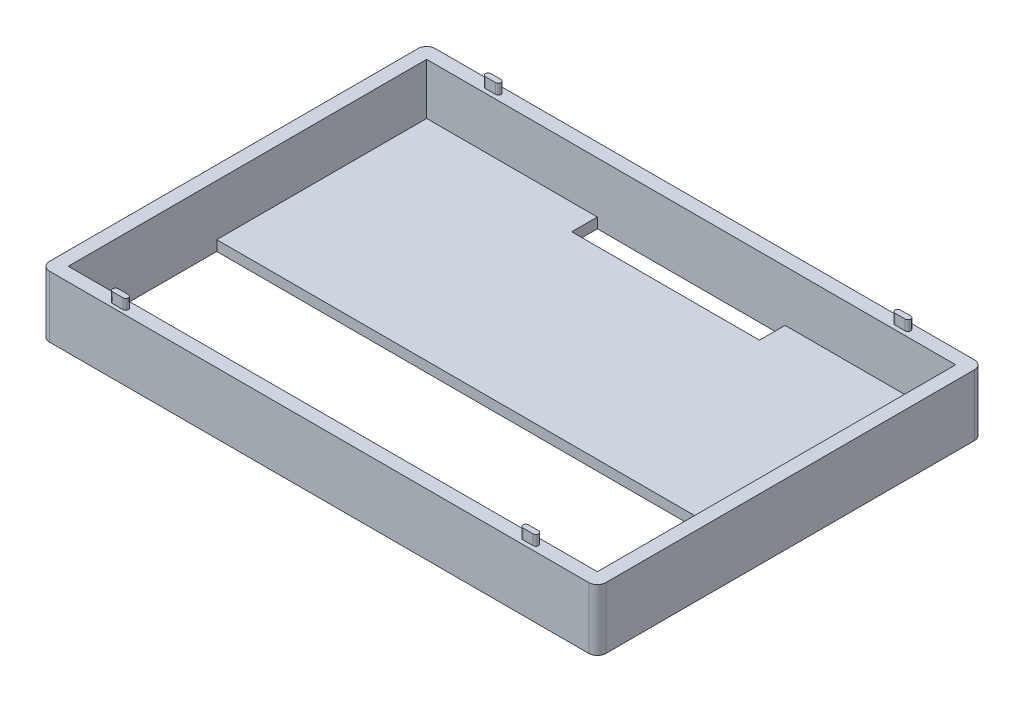
SolidWorks part; units mm, degrees
ref_plane "Front Plane" through (0, 0, 0) normal (0, 0, 1) x (1, 0, 0)
ref_plane "Top Plane" through (0, 0, 0) normal (0, 1, 0) x (1, 0, 0)
ref_plane "Right Plane" through (0, 0, 0) normal (1, 0, 0) x (0, 0, -1)
sketch "Sketch3" plane through (0, 0, 0) normal (0, 1, 0) x (1, 0, 0)
  line L1 (-81.5, 56.5) -> (81.5, 56.5)
  line L2 (-81.5, 56.5) -> (-81.5, -56.5)
  line L3 (-81.5, -56.5) -> (81.5, -56.5)
  line L4 (81.5, 56.5) -> (81.5, -56.5)
  line L5 (-81.5, 56.5) -> (81.5, -56.5) construction
  line L6 (-81.5, -56.5) -> (81.5, 56.5) construction
  point P0 (0, 0)
  dimension "D1" = 113
  dimension "D2" = 163
extrude "Boss-Extrude2" add sketch "Sketch3" along normal blind 18
sketch "Sketch4" plane through (0, 18, 0) normal (0, 1, 0) x (1, 0, 0)
  line L1 (-77.5, 52.5) -> (77.5, 52.5)
  line L2 (-77.5, 52.5) -> (-77.5, -52.5)
  line L3 (-77.5, -52.5) -> (77.5, -52.5)
  line L4 (77.5, 52.5) -> (77.5, -52.5)
  line L5 (-77.5, 52.5) -> (77.5, -52.5) construction
  line L6 (-77.5, -52.5) -> (77.5, 52.5) construction
  point P0 (0, 0)
  dimension "D1" = 105
  dimension "D2" = 155
extrude "Cut-Extrude2" cut sketch "Sketch4" against normal blind 15
fillet "Fillet1" radius 2.5 4 edges at (81.5, 9, -56.5) (-81.5, 9, -56.5) (81.5, 9, 56.5) (-81.5, 9, 56.5)
sketch "Sketch5" plane through (0, 3, 0) normal (0, 1, 0) x (1, 0, 0)
  line L0 (77.5, 52.5) -> (-77.5, 52.5) construction
  line L1 (27.5, 52.5) -> (-27.5, 52.5)
  line L2 (27.5, 52.5) -> (27.5, 45)
  line L3 (27.5, 45) -> (-27.5, 45)
  line L4 (-27.5, 52.5) -> (-27.5, 45)
  line L5 (-77.5, 52.5) -> (-77.5, -52.5) construction
  dimension "D1" = 7.5
  dimension "D2" = 55
  dimension "D3" = 50
extrude "TopWires" cut sketch "Sketch5" against normal blind 3
sketch "Sketch6" plane through (0, 3, 0) normal (0, 1, 0) x (1, 0, 0)
  line L0 (77.5, -52.5) -> (77.5, 52.5) construction
  line L1 (-77.5, -52.5) -> (77.5, -52.5)
  line L2 (-77.5, -52.5) -> (-77.5, -9)
  line L3 (-77.5, -9) -> (77.5, -9)
  line L4 (77.5, -52.5) -> (77.5, -9)
  dimension "D1" = 43.5
extrude "MotorWires" cut sketch "Sketch6" against normal blind 3
sketch "Sketch13" plane through (0, 0, 0) normal (0, -1, 0) x (-1, 0, 0)
  line L0 (61.5, 54.5) -> (58.5, 54.5) construction
  line L1 (61.5, 53.5) -> (58.5, 53.5)
  line L2 (61.5, 55.5) -> (58.5, 55.5)
  line L3 (-79, 56.5) -> (79, 56.5) construction
  line L4 (81.5, 54) -> (81.5, -54) construction
  line L5 (-58.5, 54.5) -> (-61.5, 54.5) construction
  line L6 (-58.5, 53.5) -> (-61.5, 53.5)
  line L7 (-58.5, 55.5) -> (-61.5, 55.5)
  line L8 (-81.5, -54) -> (-81.5, 54) construction
  line L9 (61.5, -54.5) -> (58.5, -54.5) construction
  line L10 (61.5, -55.5) -> (58.5, -55.5)
  line L11 (61.5, -53.5) -> (58.5, -53.5)
  line L12 (79, -56.5) -> (-79, -56.5) construction
  line L13 (-61.5, -54.5) -> (-58.5, -54.5) construction
  line L14 (-61.5, -53.5) -> (-58.5, -53.5)
  line L15 (-61.5, -55.5) -> (-58.5, -55.5)
  arc A0 (61.5, 53.5) -> (61.5, 55.5) centre (61.5, 54.5) ccw
  arc A1 (58.5, 55.5) -> (58.5, 53.5) centre (58.5, 54.5) ccw
  arc A2 (-58.5, 53.5) -> (-58.5, 55.5) centre (-58.5, 54.5) ccw
  arc A3 (-61.5, 55.5) -> (-61.5, 53.5) centre (-61.5, 54.5) ccw
  arc A4 (61.5, -55.5) -> (61.5, -53.5) centre (61.5, -54.5) ccw
  arc A5 (58.5, -53.5) -> (58.5, -55.5) centre (58.5, -54.5) ccw
  arc A6 (-61.5, -53.5) -> (-61.5, -55.5) centre (-61.5, -54.5) ccw
  arc A7 (-58.5, -55.5) -> (-58.5, -53.5) centre (-58.5, -54.5) ccw
  point P2 (60, 54.5)
  point P13 (-60, 54.5)
  point P22 (60, -54.5)
  point P31 (-60, -54.5)
  dimension "D2" = 1
  dimension "D6" = 1
  dimension "D9" = 1
  dimension "D12" = 1
  dimension "D1" = 3
  dimension "D3" = 1
  dimension "D4" = 20
  dimension "D5" = 3
  dimension "D7" = 20
  dimension "D8" = 3
  dimension "D10" = 1
  dimension "D11" = 20
  dimension "D13" = 3
extrude "ConnectorHoles" cut sketch "Sketch13" against normal blind 3
sketch "Sketch14" plane through (0, 3, 0) normal (0, 1, 0) x (1, 0, 0)
  line L1 (77.5, -9) -> (67.5, -9)
  line L2 (77.5, -9) -> (77.5, 13)
  line L3 (77.5, 13) -> (67.5, 13)
  line L4 (67.5, -9) -> (67.5, 13)
  dimension "D1" = 22
  dimension "D2" = 10
extrude "SideWires" cut sketch "Sketch14" against normal blind 3
sketch "Sketch16" plane through (0, 18, 0) normal (0, 1, 0) x (1, 0, 0)
  line L0 (61.5, -54.5) -> (58.5, -54.5) construction
  line L1 (61.5, -55.3) -> (58.5, -55.3)
  line L2 (61.5, -53.7) -> (58.5, -53.7)
  line L3 (-77.5, -52.5) -> (77.5, -52.5) construction
  line L5 (81.5, -54) -> (81.5, 54) construction
  line L6 (-58.5, -54.6919) -> (-61.5, -54.6919) construction
  line L7 (-58.5, -55.4919) -> (-61.5, -55.4919)
  line L8 (-58.5, -53.8919) -> (-61.5, -53.8919)
  line L9 (-81.5, 54) -> (-81.5, -54) construction
  line L10 (-61.5, 54.5) -> (-58.5, 54.5) construction
  line L11 (-61.5, 55.3) -> (-58.5, 55.3)
  line L12 (-61.5, 53.7) -> (-58.5, 53.7)
  line L13 (61.5, 54.5) -> (58.5, 54.5) construction
  line L14 (61.5, 53.7) -> (58.5, 53.7)
  line L15 (61.5, 55.3) -> (58.5, 55.3)
  line L16 (79, 56.5) -> (-79, 56.5) construction
  arc A0 (61.5, -55.3) -> (61.5, -53.7) centre (61.5, -54.5) ccw
  arc A1 (58.5, -53.7) -> (58.5, -55.3) centre (58.5, -54.5) ccw
  arc A2 (-58.5, -55.4919) -> (-58.5, -53.8919) centre (-58.5, -54.6919) ccw
  arc A3 (-61.5, -53.8919) -> (-61.5, -55.4919) centre (-61.5, -54.6919) ccw
  arc A4 (-61.5, 55.3) -> (-61.5, 53.7) centre (-61.5, 54.5) ccw
  arc A5 (-58.5, 53.7) -> (-58.5, 55.3) centre (-58.5, 54.5) ccw
  arc A6 (61.5, 53.7) -> (61.5, 55.3) centre (61.5, 54.5) ccw
  arc A7 (58.5, 55.3) -> (58.5, 53.7) centre (58.5, 54.5) ccw
  point P2 (60, -54.5)
  point P13 (-60, -54.6919)
  point P22 (-60, 54.5)
  point P29 (60, 54.5)
  point P34 (0, 0)
  dimension "D2" = 0.8
  dimension "D6" = 0.8
  dimension "D8" = 0.8
  dimension "D13" = 0.8
  dimension "D1" = 3
  dimension "D3" = 1.2
  dimension "D4" = 20
  dimension "D5" = 3
  dimension "D7" = 20
  dimension "D9" = 3
  dimension "D10" = 20
  dimension "D11" = 20
  dimension "D12" = 3
  dimension "D14" = 1.2
  dimension "D15" = 1.2
extrude "Boss-Extrude7" add sketch "Sketch16" along normal blind 3
